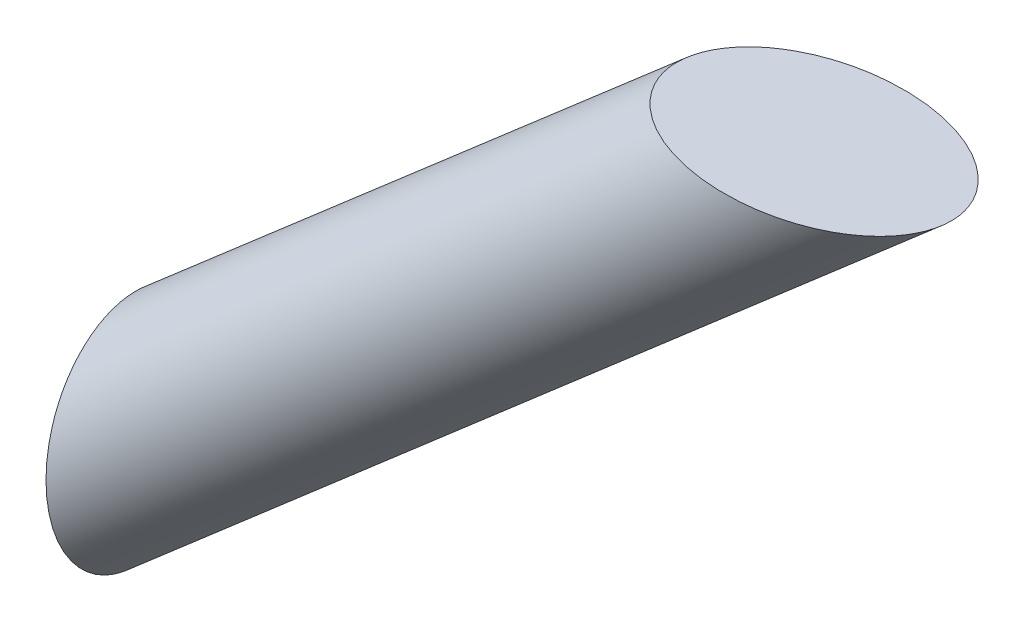
SolidWorks part; units mm, degrees
ref_plane "Front Plane" through (0, 0, 0) normal (0, 0, 1) x (1, 0, 0)
ref_plane "Top Plane" through (0, 0, 0) normal (0, 1, 0) x (1, 0, 0)
ref_plane "Right Plane" through (0, 0, 0) normal (1, 0, 0) x (0, 0, -1)
sketch "Sketch1" plane through (0, 0, 0) normal (0, 0, 1) x (1, 0, 0)
  line L0 (135.6058, 117.0111) -> (-94.788, -82.5427)
  dimension "D1" = 304.8
revolve "Revolve-Thin1" add sketch "Sketch1" angle 360 about L0 wall 25.4
sketch "Sketch2" plane through (0, 0, 0) normal (0, 0, 1) x (1, 0, 0)
  line L4 (180.0397, 97.8116) -> (7.4801, 97.8116)
  line L5 (7.4801, 97.8116) -> (101.4116, 186.9937)
  line L6 (101.4116, 186.9937) -> (180.0397, 97.8116)
extrude "Cut-Extrude1" cut sketch "Sketch2" against normal through all both and the other way through all
sketch "Sketch3" plane through (0, 0, 0) normal (0, 0, 1) x (1, 0, 0)
  line L0 (-78.1586, -101.7422) -> (-78.1586, 0)
  line L1 (-78.1586, 0) -> (-164.4242, -9.2605)
  line L2 (-164.4242, -9.2605) -> (-121.2914, -114.5068)
  line L3 (-121.2914, -114.5068) -> (-78.1586, -101.7422)
extrude "Cut-Extrude2" cut sketch "Sketch3" against normal through all both and the other way through all
